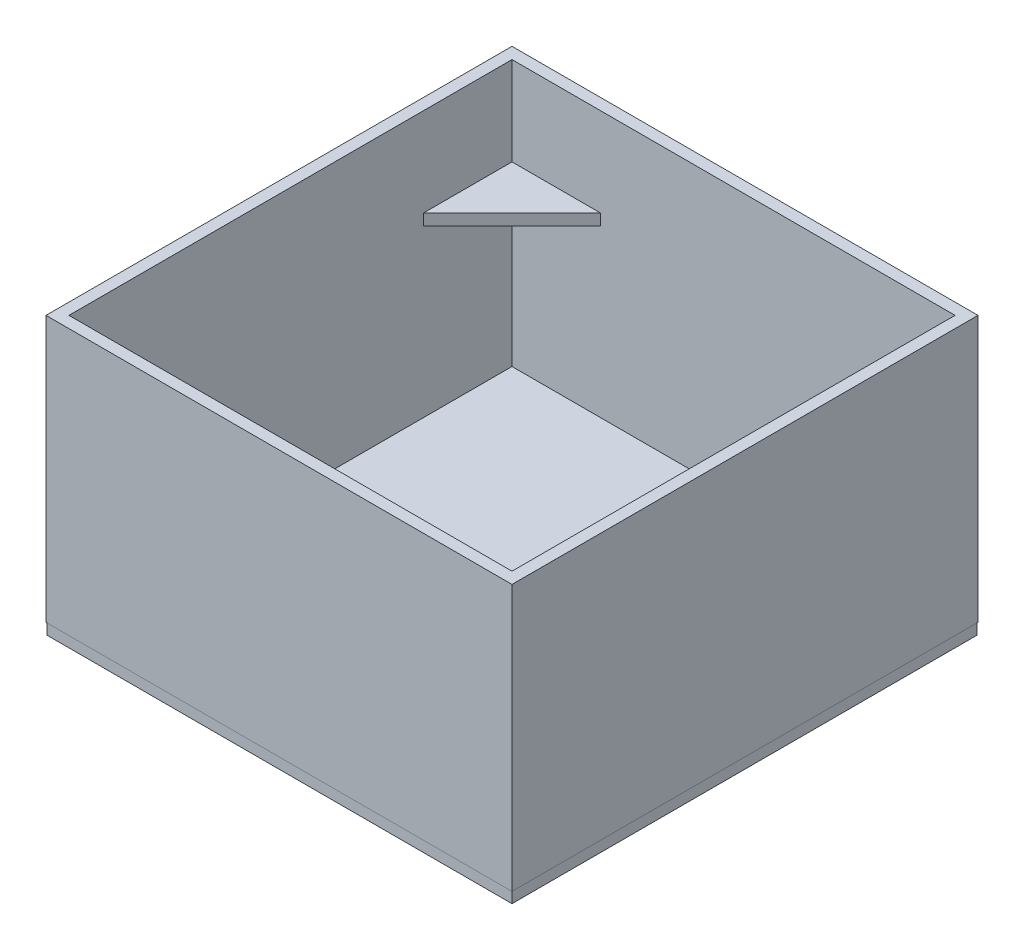
SolidWorks part; units mm, degrees
ref_plane "Front Plane" through (0, 0, 0) normal (0, 0, 1) x (1, 0, 0)
ref_plane "Top Plane" through (0, 0, 0) normal (0, 1, 0) x (1, 0, 0)
ref_plane "Right Plane" through (0, 0, 0) normal (1, 0, 0) x (0, 0, -1)
sketch "Sketch1" plane through (0, 0, 0) normal (0, 1, 0) x (1, 0, 0)
  line L0 (-77.2657, 77.1769) -> (56.0843, 77.1769)
  line L1 (56.0843, 77.1769) -> (56.0843, -56.1731)
  line L2 (56.0843, -56.1731) -> (-77.2657, -56.1731)
  line L3 (-77.2657, -56.1731) -> (-77.2657, 77.1769)
  dimension "D1" = 133.35
  dimension "D2" = 133.35
extrude "Boss-Extrude2" add sketch "Sketch1" along normal blind 3.175 contours L0 L1 L2 L3
sketch "Sketch2" plane through (0, 3.175, 0) normal (0, 1, 0) x (1, 0, 0)
  line L0 (-74.0907, 74.0019) -> (52.9093, 74.0019)
  line L1 (52.9093, 74.0019) -> (52.9093, -52.9981)
  line L2 (52.9093, -52.9981) -> (-74.0907, -52.9981)
  line L3 (-74.0907, 74.0019) -> (-74.0907, -52.9981)
  line L4 (-77.2657, 77.1769) -> (-77.2657, -56.1731)
  line L5 (-77.2657, -56.1731) -> (56.0843, -56.1731)
  line L6 (56.0843, -56.1731) -> (56.0843, 77.1769)
  line L7 (56.0843, 77.1769) -> (56.0843, -56.1731) construction
  line L8 (-77.2657, 77.1769) -> (56.0843, 77.1769) construction
  line L9 (-77.2657, 77.1769) -> (-77.2657, -56.1731)
  line L10 (-77.2657, 77.1769) -> (56.0843, 77.1769)
  point P8 (0, 0)
  dimension "D1" = 3.175
  dimension "D2" = 3.175
  dimension "D3" = 3.175
  dimension "D4" = 3.175
extrude "Extrude-Thin1" add sketch "Sketch2" along normal blind 76.2 thin contours L3 L2 L1 L0
sketch "Sketch4" plane through (0, 79.375, 0) normal (0, 1, 0) x (1, 0, 0)
  line L0 (-48.6907, 74.0019) -> (-74.0907, 48.6019)
  line L1 (-74.0907, 74.0019) -> (52.9093, 74.0019) construction
  line L2 (-74.0907, 74.0019) -> (-74.0907, -52.9981) construction
  line L3 (-74.0907, 48.6019) -> (-74.0907, 74.0019)
  line L4 (-74.0907, 74.0019) -> (-48.6907, 74.0019)
  line L5 (-74.0907, -52.9981) -> (-74.0907, -27.5981)
  line L6 (-74.0907, -27.5981) -> (-48.6907, -52.9981)
  line L7 (52.9093, -52.9981) -> (-74.0907, -52.9981) construction
  line L8 (-74.0907, -52.9981) -> (-48.6907, -52.9981)
  line L9 (52.9093, 74.0019) -> (27.5093, 74.0019)
  line L10 (27.5093, 74.0019) -> (52.9093, 48.6019)
  line L11 (52.9093, 74.0019) -> (52.9093, -52.9981) construction
  line L12 (52.9093, 48.6019) -> (52.9093, 74.0019)
  line L13 (52.9093, -52.9981) -> (52.9093, -27.5981)
  line L14 (52.9093, -27.5981) -> (27.5093, -52.9981)
  line L15 (27.5093, -52.9981) -> (52.9093, -52.9981)
  dimension "D1" = 25.4
  dimension "D2" = 25.4
  dimension "D3" = 25.4
  dimension "D4" = 25.4
  dimension "D5" = 25.4
  dimension "D6" = 25.4
  dimension "D7" = 25.4
extrude "Boss-Extrude3" add sketch "Sketch4" against normal blind 3.175 from offset 25.4
